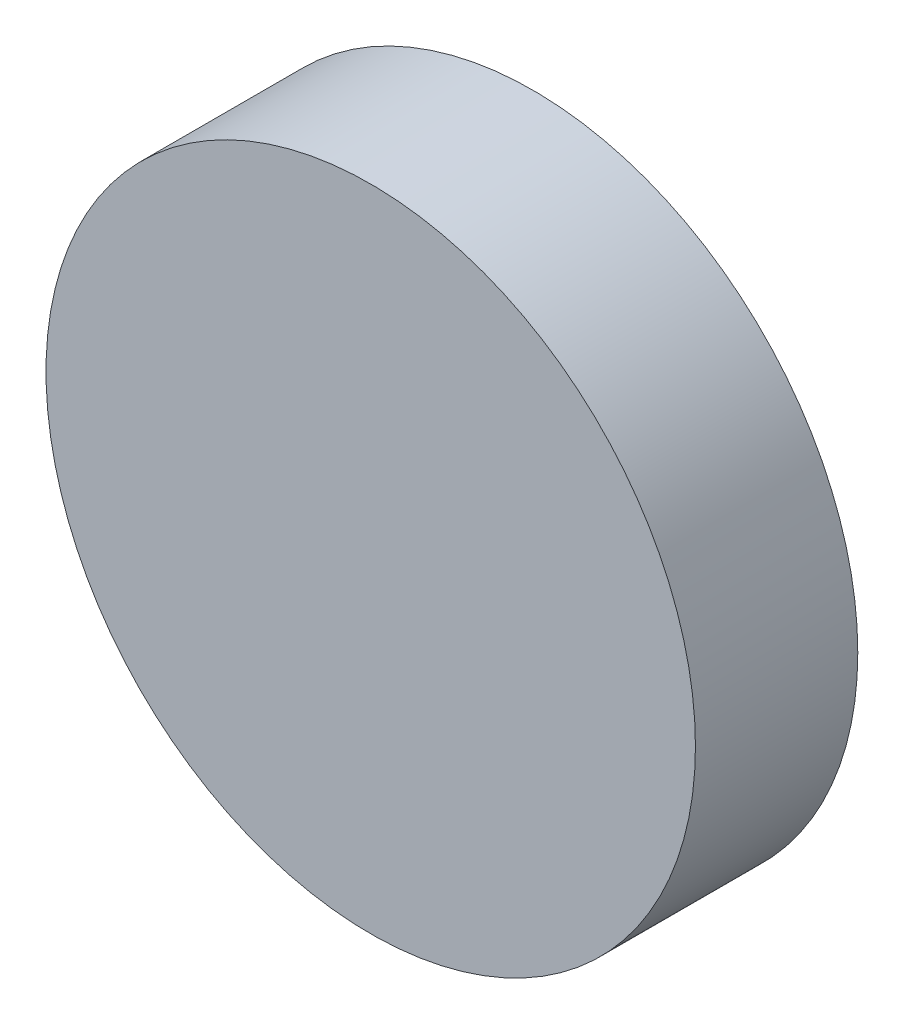
SolidWorks part; units mm, degrees
ref_plane "Plan de face" through (0, 0, 0) normal (0, 0, 1) x (1, 0, 0)
ref_plane "Plan de dessus" through (0, 0, 0) normal (0, 1, 0) x (1, 0, 0)
ref_plane "Plan de droite" through (0, 0, 0) normal (1, 0, 0) x (0, 0, -1)
sketch "Esquisse1" plane through (0, 0, 0) normal (0, 0, 1) x (1, 0, 0)
  circle A0 centre (0, 0) radius 25.4
extrude "Boss.-Extru.1" add sketch "Esquisse1" along normal blind 12.7
